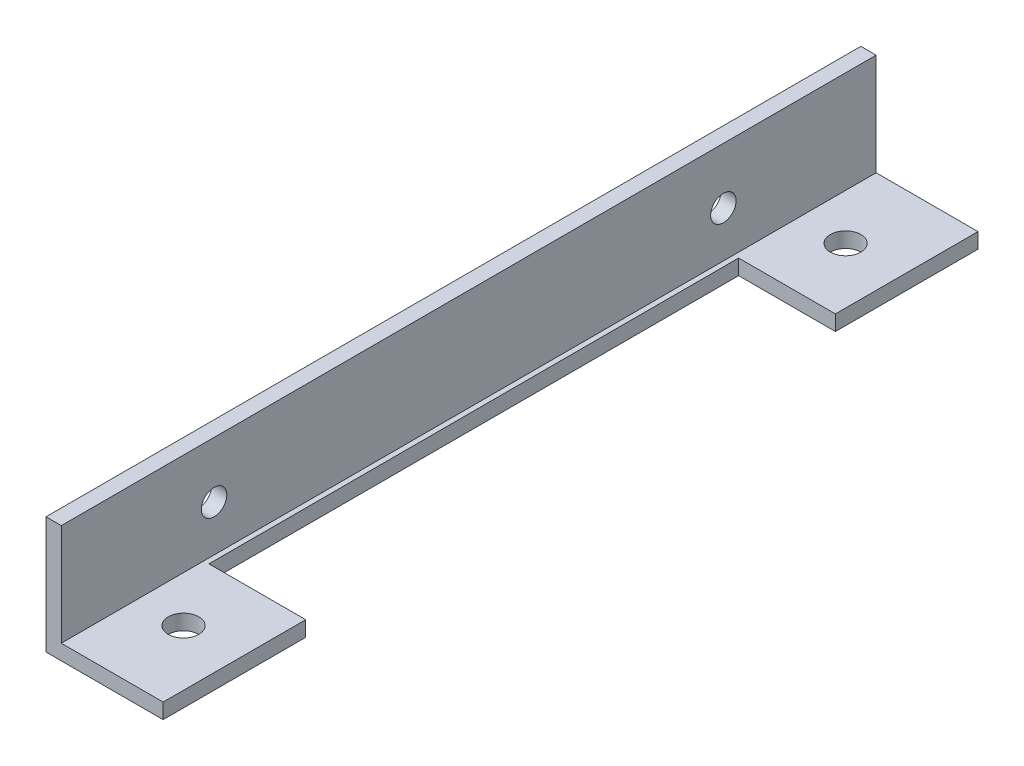
SolidWorks part; units mm, degrees
material "3.0205 (EN-AW 1200)"
ref_plane "Plan de face" through (0, 0, 0) normal (0, 0, 1) x (1, 0, 0)
ref_plane "Plan de dessus" through (0, 0, 0) normal (0, 1, 0) x (1, 0, 0)
ref_plane "Plan de droite" through (0, 0, 0) normal (1, 0, 0) x (0, 0, -1)
sketch "Esquisse1" plane through (0, 0, 0) normal (0, 0, 1) x (1, 0, 0)
  line L0 (0, 11.5) -> (0, 0)
  line L1 (0, 0) -> (11.5, 0)
  dimension "D1" = 11.5
  dimension "D2" = 11.5
extrude "Extru.-Mince1" add sketch "Esquisse1" along normal blind 80 thin thin type one direction reverse wall 1.5
sketch "Esquisse2" plane through (0, 0, 0) normal (-1, 0, 0) x (0, 0, 1)
  line L0 (40, 0) -> (40, 11.5) construction
  line L1 (80, 0) -> (0, 0) construction
  line L2 (80, 11.5) -> (0, 11.5) construction
  circle A0 centre (15, 6) radius 1.25
  circle A1 centre (65, 6) radius 1.25
  dimension "D1" = 2.5
  dimension "D2" = 50
  dimension "D3" = 6
extrude "Enlèv. mat.-Extru.1" cut sketch "Esquisse2" against normal blind 10
sketch "Esquisse3" plane through (0, 0, 0) normal (0, -1, 0) x (1, 0, 0)
  line L0 (11.5, 80) -> (11.5, 0) construction
  line L1 (0, 40) -> (11.5, 40) construction
  line L2 (2, 66) -> (2, 14)
  line L3 (2, 14) -> (11.5, 14)
  line L4 (11.5, 66) -> (11.5, 14)
  line L5 (0, 80) -> (0, 0) construction
  line L6 (2, 66) -> (11.5, 66)
  circle A0 centre (6, 7.5) radius 1.5
  circle A1 centre (6, 72.5) radius 1.5
  dimension "D1" = 65
  dimension "D2" = 6
  dimension "D3" = 3
  dimension "D4" = 2
  dimension "D5" = 52
extrude "Enlèv. mat.-Extru.2" cut sketch "Esquisse3" against normal blind 10
